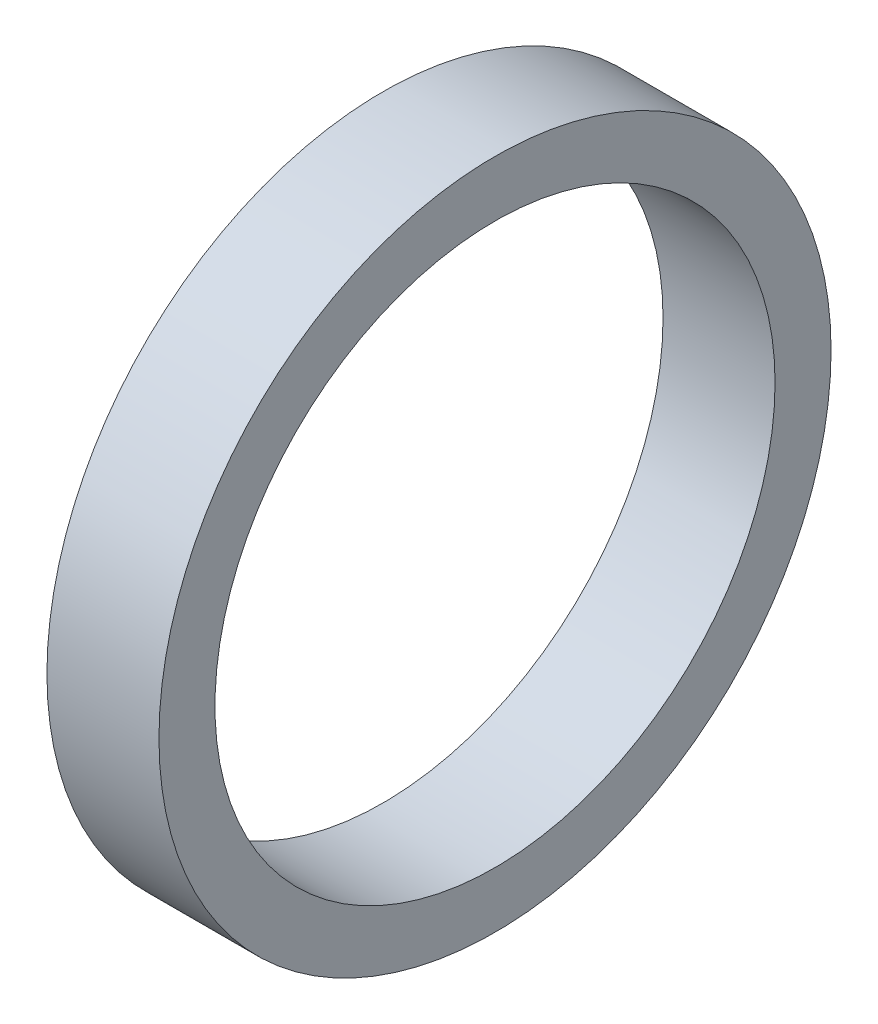
SolidWorks part; units mm, degrees
ref_plane "Спереди" through (0, 0, 0) normal (0, 0, 1) x (1, 0, 0)
ref_plane "Сверху" through (0, 0, 0) normal (0, 1, 0) x (1, 0, 0)
ref_plane "Справа" through (0, 0, 0) normal (1, 0, 0) x (0, 0, -1)
sketch "Эскиз1" plane through (0, 0, 0) normal (1, 0, 0) x (0, 0, -1)
  circle A0 centre (0, 0) radius 7.5
  circle A1 centre (0, 0) radius 9
  dimension "D1" = 15
  dimension "D2" = 18
extrude "Бобышка-Вытянуть1" add sketch "Эскиз1" along normal blind 3
